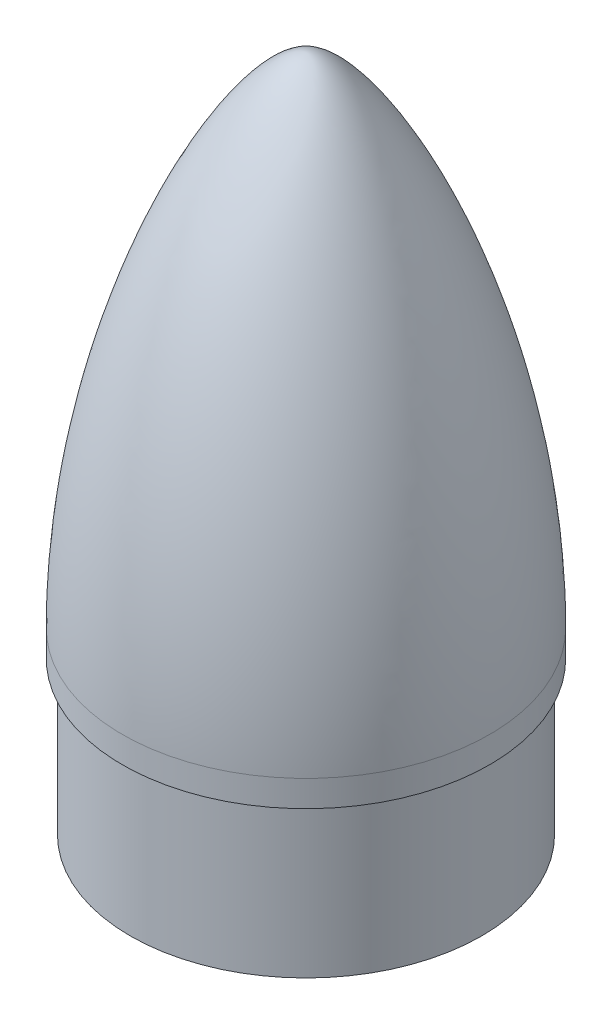
SolidWorks part; units mm, degrees
ref_plane "Front Plane" through (0, 0, 0) normal (0, 0, 1) x (1, 0, 0)
ref_plane "Top Plane" through (0, 0, 0) normal (0, 1, 0) x (1, 0, 0)
ref_plane "Right Plane" through (0, 0, 0) normal (1, 0, 0) x (0, 0, -1)
sketch "Sketch1" plane through (0, 0, 0) normal (0, 0, 1) x (1, 0, 0)
  line L0 (0, 0) -> (0, 78.608) construction
  line L1 (-33.5, 0) -> (-33.5, 29)
  line L2 (-33.5, 29) -> (-35, 29)
  line L3 (-35, 29) -> (-35, 34)
  line L5 (-32.5, 0) -> (-32.5, 30)
  line L6 (-32.5, 30) -> (-34, 30)
  line L7 (-34, 30) -> (-34, 33.6787)
  line L9 (-33.5, 0) -> (-32.5, 0)
  line L11 (-35, 34) -> (-9.4173, 69.6948) construction
  line L12 (-34, 33.6787) -> (-8.6045, 69.1123) construction
  line L13 (-35, 39.7218) -> (-35, 7.8137) construction
  line L14 (16.3696, 129) -> (-16.3696, 129) construction
  line L15 (-33.9985, 34.6787) -> (-33.9985, 34.6787)
  line L16 (-33.9985, 34.6787) -> (-33.9985, 34.6787)
  line L17 (-33.9985, 34.6787) -> (-33.9985, 34.6787)
  line L18 (-33.9985, 34.6787) -> (-33.9985, 34.6787)
  line L19 (-33.9985, 34.6787) -> (-33.9985, 34.6787)
  line L20 (-33.9985, 34.6787) -> (-33.9985, 34.6787)
  line L21 (-33.9985, 34.6787) -> (-33.9985, 34.6787)
  line L22 (-34, 33.6787) -> (-33.9985, 34.6787)
  line L23 (0, 129) -> (0, 128)
  spline S0 degree 3 poles (-35, 34) (-35, 84.2305) (-10.2041, 129) (0, 129) knots 0 0 0 0 1 1 1 1
  spline S1 degree 1 poles (-33.9985, 34.6787) (0, 128) knots 0 0 1 1 construction
  spline S2 degree 3 poles (-33.9985, 34.6787) (-33.9916, 36.2241) (-33.9304, 39.323) (-33.628, 45.4497) (-32.9301, 52.9999) (-31.6372, 61.8164) (-29.3814, 73.1748) (-25.7059, 86.4831) (-20.3818, 100.5699) (-15.5663, 110.3537) (-11.7216, 116.7724) (-8.9033, 120.8218) (-6.2163, 124.0441) (-4.1491, 125.9853) (-2.6527, 127.0595) (-1.6281, 127.6205) (-0.8799, 127.8851) (-0.3487, 127.9845) (-0.1195, 128) (0, 128) knots 0.004535 0.004535 0.004535 0.004535 0.035644 0.066752 0.128969 0.191185 0.253402 0.377835 0.502268 0.626701 0.688917 0.751134 0.81335 0.875567 0.906675 0.937783 0.968892 0.984446 1 1 1 1
  dimension "D2" = 30
  dimension "D3" = 1.5
  dimension "D4" = 5
  dimension "D6" = 95
  dimension "D7" = 70
  dimension "D1" = 1
  dimension "D5" = 1
revolve "Revolve1" add sketch "Sketch1" angle 360 about L0
sketch "Sketch2" plane through (0, 0, 0) normal (0, -1, 0) x (1, 0, 0)
  circle A0 centre (0, 0) radius 33.5 construction
  circle A1 centre (0, 0) radius 33.5
extrude "Boss-Extrude1" add sketch "Sketch2" against normal blind 2
sketch "Sketch3" plane through (0, 0, 0) normal (0, -1, 0) x (1, 0, 0)
  line L0 (0, 7.6543) -> (0, -9.5899) construction
  line L1 (-7.0824, 0) -> (5.6747, 0) construction
  line L2 (12.5, -7.5) -> (2.5, -7.5)
  line L3 (-12.5, 7.5) -> (-2.5, 7.5)
  line L4 (-12.5, 7.5) -> (-12.5, -7.5)
  line L5 (-12.5, -7.5) -> (-2.5, -7.5)
  line L6 (-2.5, 7.5) -> (-2.5, -7.5)
  line L7 (-12.5, 7.5) -> (-2.5, -7.5) construction
  line L8 (-12.5, -7.5) -> (-2.5, 7.5) construction
  line L9 (2.5, 7.5) -> (2.5, -7.5)
  line L10 (12.5, 7.5) -> (2.5, 7.5)
  line L11 (12.5, 7.5) -> (12.5, -7.5)
  point P5 (-7.5, 0)
  dimension "D1" = 10
  dimension "D2" = 15
  dimension "D3" = 5
extrude "Cut-Extrude1" cut sketch "Sketch3" against normal blind 2
